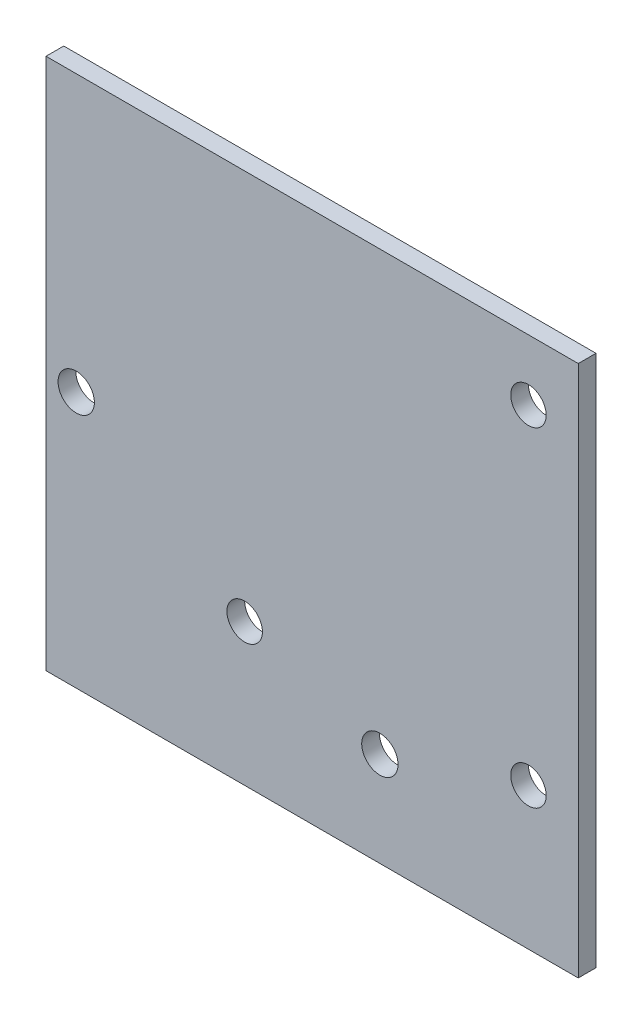
SolidWorks part; units mm, degrees
ref_plane "Front Plane" through (0, 0, 0) normal (0, 0, 1) x (1, 0, 0)
ref_plane "Top Plane" through (0, 0, 0) normal (0, 1, 0) x (1, 0, 0)
ref_plane "Right Plane" through (0, 0, 0) normal (1, 0, 0) x (0, 0, -1)
sketch "Sketch1" plane through (0, 0, 0) normal (0, 0, 1) x (1, 0, 0)
  line L0 (-90.0979, 125.73) -> (-39.2979, 125.73) construction
  line L1 (-16.486, 187.7858) -> (-111.76, 187.7858)
  line L2 (-16.486, 187.7858) -> (-16.486, 92.5286)
  line L3 (-16.486, 92.5286) -> (-111.76, 92.5286)
  line L4 (-111.76, 187.7858) -> (-111.76, 92.5286)
  line L5 (-39.2979, 125.73) -> (-39.2979, 176.53) construction
  line L6 (-90.0979, 176.53) -> (-90.0979, 125.73) construction
  circle A0 centre (-25.4, 176.8929) radius 3.175
  circle A1 centre (-25.4, 117.9286) radius 3.175
  circle A2 centre (-76.2, 117.9286) radius 3.175
  circle A3 centre (-51.9979, 109.474) radius 3.2512
  circle A4 centre (-106.3539, 138.43) radius 3.2512
  dimension "D1" = 6.35
  dimension "D2" = 6.35
  dimension "D3" = 6.35
  dimension "D10" = 6.5024
  dimension "D4" = 8.914
  dimension "D5" = 10.893
  dimension "D6" = 35.56
  dimension "D7" = 25.4
  dimension "D8" = 16.256
  dimension "D9" = 12.7
  dimension "D11" = 16.256
  dimension "D12" = 12.7
extrude "Boss-Extrude1" add sketch "Sketch1" along normal blind 3.175
equation "\"80/20 to Center Hole\"= .64in"
equation "\"80/20 from Edge\"= 0.5in"
equation "\"D8@Sketch1\"=\"80/20 to Center Hole\""
equation "\"D9@Sketch1\"=\"80/20 from Edge\""
equation "\"D11@Sketch1\"=\"80/20 to Center Hole\""
equation "\"D12@Sketch1\"=\"80/20 from Edge\""
